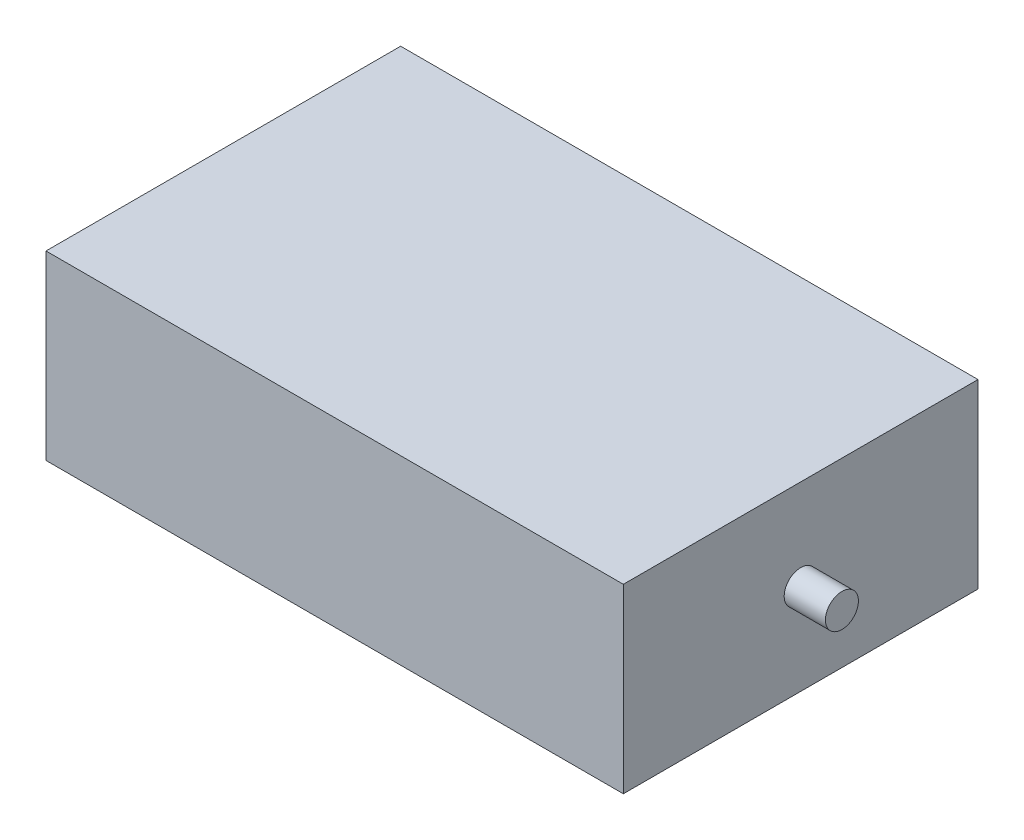
SolidWorks part; units mm, degrees
ref_plane "Front Plane" through (0, 0, 0) normal (0, 0, 1) x (1, 0, 0)
ref_plane "Top Plane" through (0, 0, 0) normal (0, 1, 0) x (1, 0, 0)
ref_plane "Right Plane" through (0, 0, 0) normal (1, 0, 0) x (0, 0, -1)
sketch "Sketch1" plane through (0, 0, 0) normal (0, 1, 0) x (1, 0, 0)
  line L1 (-35, -21.5) -> (35, -21.5)
  line L2 (-35, -21.5) -> (-35, 21.5)
  line L3 (-35, 21.5) -> (35, 21.5)
  line L4 (35, -21.5) -> (35, 21.5)
  line L5 (-35, -21.5) -> (35, 21.5) construction
  line L6 (-35, 21.5) -> (35, -21.5) construction
  point P0 (0, 0)
  dimension "D1" = 70
  dimension "D2" = 43
extrude "Boss-Extrude1" add sketch "Sketch1" along normal blind 22
sketch "Sketch2" plane through (0, 0, 0) normal (0, -1, 0) x (1, 0, 0)
  text T0 "MOTOR"
extrude "Cut-Extrude1" cut sketch "Sketch2" against normal blind 1
sketch "Sketch3" plane through (35, 0, 0) normal (1, 0, 0) x (0, 0, -1)
  circle A0 centre (0, 11) radius 2
  dimension "D1" = 4
extrude "Boss-Extrude2" add sketch "Sketch3" along normal blind 5
